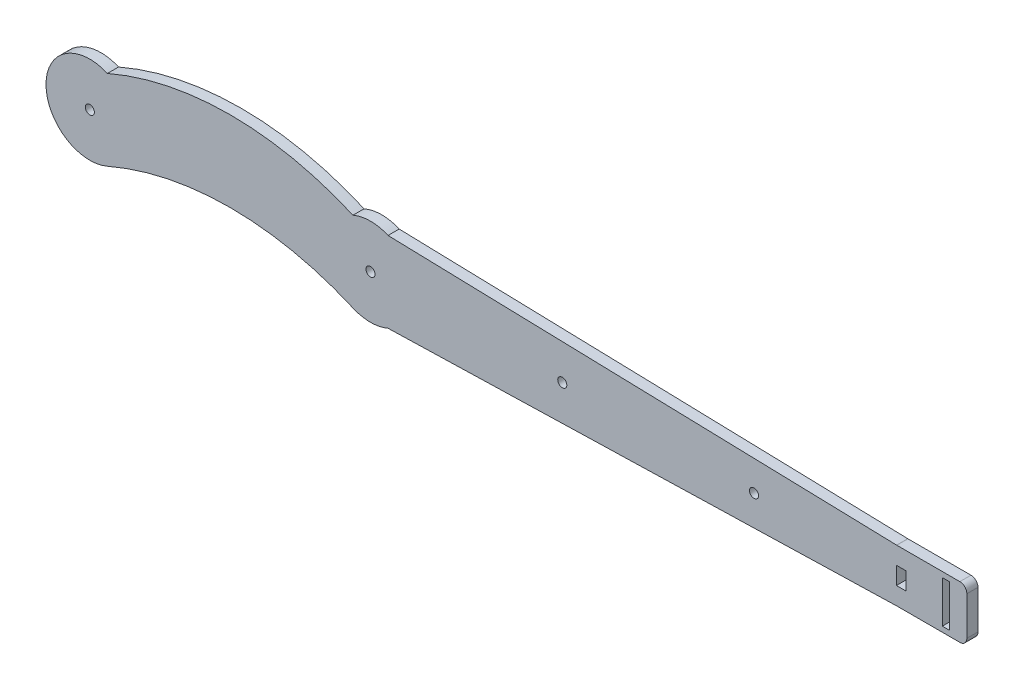
SolidWorks part; units mm, degrees
ref_plane "Front Plane" through (0, 0, 0) normal (0, 0, 1) x (1, 0, 0)
ref_plane "Top Plane" through (0, 0, 0) normal (0, 1, 0) x (1, 0, 0)
ref_plane "Right Plane" through (0, 0, 0) normal (1, 0, 0) x (0, 0, -1)
sketch "Sketch1" plane through (0, 0, 0) normal (0, 0, 1) x (1, 0, 0)
  line L0 (150, 7.5) -> (5, 11.4564)
  line L1 (150, 7.5) -> (170, 7.5)
  line L2 (170, 7.5) -> (170, -7.5)
  line L3 (170, -7.5) -> (150, -7.5)
  line L5 (-40, -68.7386) -> (-40, -91.6515) construction
  line L6 (-80, 0) -> (170, 0) construction
  line L7 (150, 7.5) -> (150, -7.5) construction
  line L8 (5, -11.4564) -> (150, -7.5)
  line L9 (-75, 11.4564) -> (-75, -11.4564) construction
  line L10 (-75, -11.4564) -> (-5, -11.4564) construction
  line L11 (-5, -11.4564) -> (-5, 11.4564) construction
  line L12 (-5, 11.4564) -> (-75, 11.4564) construction
  line L13 (-5, 11.4564) -> (5, 11.4564) construction
  line L14 (5, 11.4564) -> (5, -11.4564) construction
  line L15 (5, -11.4564) -> (-5, -11.4564) construction
  arc A0 (-5, -11.4564) -> (5, -11.4564) centre (0, 0) ccw
  arc A1 (-75, 11.4564) -> (-75, -11.4564) centre (-80, 0) ccw
  arc A2 (-5, -11.4564) -> (-75, -11.4564) centre (-40, -91.6515) ccw
  arc A3 (-5, 11.4564) -> (-75, 11.4564) centre (-40, -68.7386) ccw
  arc A4 (5, 11.4564) -> (-5, 11.4564) centre (0, 0) ccw
  dimension "D5" = 25
  dimension "D1" = 80
  dimension "D2" = 150
  dimension "D3" = 20
  dimension "D4" = 15
  dimension "D6" = 5
extrude "Boss-Extrude1" add sketch "Sketch1" along normal blind 3.175
sketch "Sketch2" plane through (0, 0, 3.175) normal (0, 0, 1) x (1, 0, 0)
  line L0 (-92.5, 0) -> (170, 0) construction
  line L1 (163, 6) -> (165, 6)
  line L2 (163, 6) -> (163, -6)
  line L3 (163, -6) -> (165, -6)
  line L4 (165, 6) -> (165, -6)
  line L5 (170, -7.5) -> (170, 7.5) construction
  line L6 (0, 0) -> (0, 6.75) construction
  line L7 (0, 6.75) -> (54.6667, 6.75) construction
  line L8 (164, 6.75) -> (164, 6) construction
  line L9 (54.6667, 6.75) -> (109.3333, 6.75) construction
  line L10 (109.3333, 6.75) -> (109.3333, 0) construction
  line L11 (109.3333, 6.75) -> (164, 6.75) construction
  line L12 (54.6667, 6.75) -> (54.6667, 0) construction
  line L13 (170, 7.5) -> (150, 7.5) construction
  line L15 (149.925, 2.5) -> (152.675, 2.5)
  line L16 (149.925, 2.5) -> (149.925, -2.5)
  line L17 (149.925, -2.5) -> (152.675, -2.5)
  line L18 (152.675, 2.5) -> (152.675, -2.5)
  circle A0 centre (-80, 0) radius 1.2925
  circle A2 centre (54.6667, 0) radius 1.2925
  circle A3 centre (109.3333, 0) radius 1.2925
  arc A4 (-75, 11.4564) -> (-75, -11.4564) centre (-80, 0) ccw construction
  circle A5 centre (0, 0) radius 1.2925
  point P14 (163, 0)
  point P33 (151.3, 2.5)
  point P34 (149.925, 0)
  dimension "D2" = 2.585
  dimension "D1" = 5
  dimension "D3" = 2
  dimension "D4" = 12
  dimension "D5" = 11.7
  dimension "D6" = 2.75
  dimension "D7" = 5
extrude "Cut-Extrude1" cut sketch "Sketch2" against normal through all
fillet "Fillet1" radius 2 4 edges at (150, -7.5, 1.5875) (150, 7.5, 1.5875) (170, -7.5, 1.5875) (170, 7.5, 1.5875)
